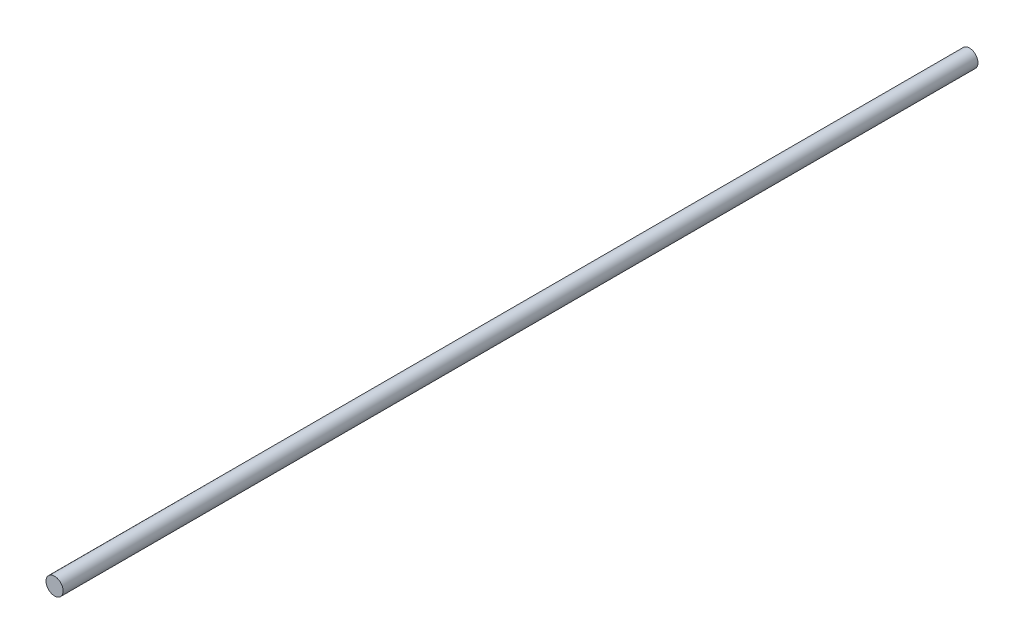
SolidWorks part; units mm, degrees
ref_plane "前视基准面" through (0, 0, 0) normal (0, 0, 1) x (1, 0, 0)
ref_plane "上视基准面" through (0, 0, 0) normal (0, 1, 0) x (1, 0, 0)
ref_plane "右视基准面" through (0, 0, 0) normal (1, 0, 0) x (0, 0, -1)
sketch "草图1" plane through (0, 0, 0) normal (0, 0, 1) x (1, 0, 0)
  circle A0 centre (0, 0) radius 4.7625
  dimension "D1" = 9.525
extrude "凸台-拉伸1" add sketch "草图1" along normal blind 508 contours A0
